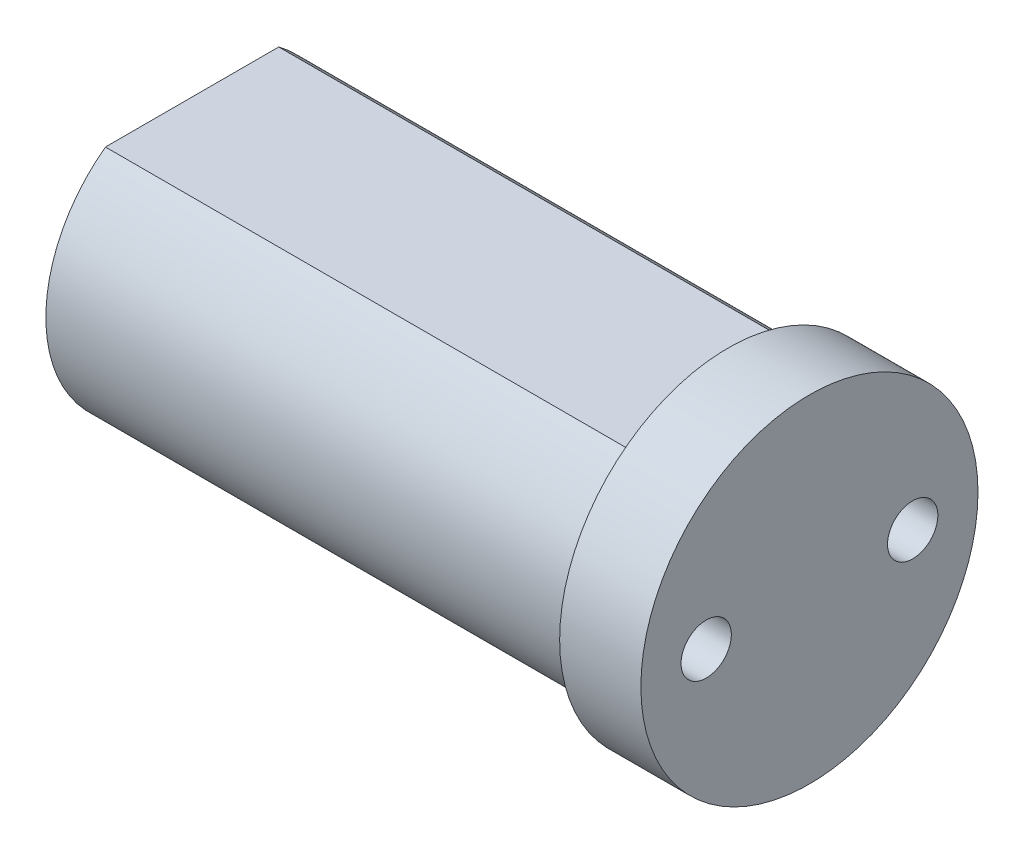
SolidWorks part; units mm, degrees
ref_plane "Спереди" through (0, 0, 0) normal (0, 0, 1) x (1, 0, 0)
ref_plane "Сверху" through (0, 0, 0) normal (0, 1, 0) x (1, 0, 0)
ref_plane "Справа" through (0, 0, 0) normal (1, 0, 0) x (0, 0, -1)
sketch "Эскиз1" plane through (0, 0, 0) normal (1, 0, 0) x (0, 0, -1)
  line L0 (0, 0) -> (0, 4.15) construction
  circle A0 centre (0, 0) radius 4.15
  dimension "D1" = 8.3
extrude "Бобышка-Вытянуть1" add sketch "Эскиз1" along normal blind 2
sketch "Эскиз2" plane through (0, 0, 0) normal (-1, 0, 0) x (0, 0, 1)
  line L0 (2.1331, 2.9) -> (-2.1331, 2.9)
  line L1 (0, 0) -> (3.6, 0) construction
  line L2 (2.1331, -2.9) -> (-2.1331, -2.9)
  circle A0 centre (0, 0) radius 3.6 construction
  arc A1 (-2.1331, -2.9) -> (-2.1331, 2.9) centre (0, 0) cw
  arc A2 (2.1331, 2.9) -> (2.1331, -2.9) centre (0, 0) cw
  dimension "D1" = 7.2
  dimension "D2" = 5.8
extrude "Бобышка-Вытянуть2" add sketch "Эскиз2" along normal blind 13.2
sketch "Эскиз3" plane through (0, 0, 0) normal (1, 0, 0) x (0, 0, -1)
  line L0 (0, 0) -> (0, 2.1526) construction
  circle A0 centre (-2.5419, 0) radius 0.6193
  circle A1 centre (2.5419, 0) radius 0.6193
extrude "Вырез-Вытянуть1" cut sketch "Эскиз3" against normal through all and the other way through all
